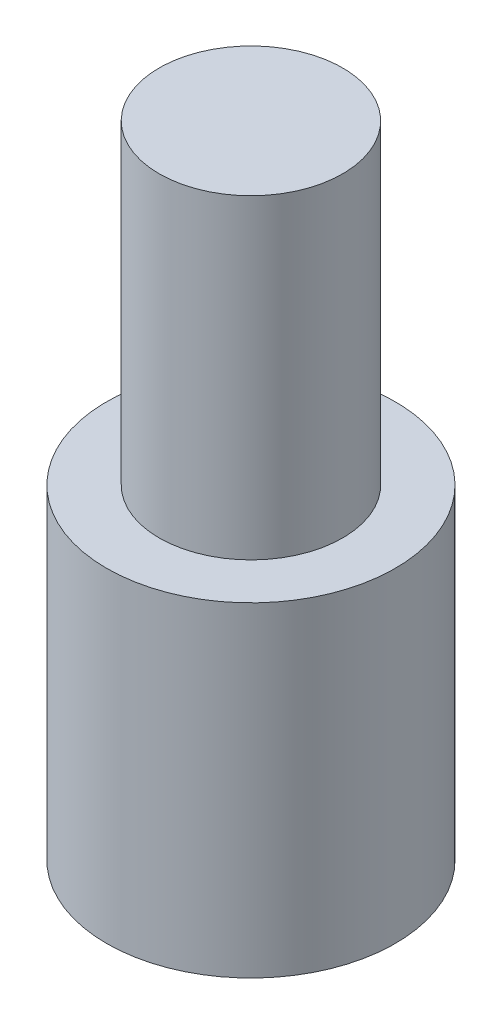
SolidWorks part; units mm, degrees
ref_plane "前视基准面" through (0, 0, 0) normal (0, 0, 1) x (1, 0, 0)
ref_plane "上视基准面" through (0, 0, 0) normal (0, 1, 0) x (1, 0, 0)
ref_plane "右视基准面" through (0, 0, 0) normal (1, 0, 0) x (0, 0, -1)
sketch "草图1" plane through (0, 0, 0) normal (0, 1, 0) x (1, 0, 0)
  circle A0 centre (-14.4643, 6.7518) radius 7.55
  dimension "D1" = 15.1
extrude "凸台-拉伸1" add sketch "草图1" along normal blind 17
sketch "草图2" plane through (0, 0, 0) normal (0, -1, 0) x (1, 0, 0)
  circle A0 centre (-14.4643, -6.7518) radius 5.15
  circle A1 centre (-14.4643, -6.7518) radius 7.55 construction
  point P2 (0, 0)
  dimension "D1" = 10.3
extrude "切除-拉伸1" cut sketch "草图2" against normal blind 2
sketch "草图3" plane through (0, 17, 0) normal (0, 1, 0) x (1, 0, 0)
  circle A0 centre (-14.4643, 6.7518) radius 4.8
  circle A1 centre (-14.4643, 6.7518) radius 7.55 construction
  dimension "D1" = 9.6
extrude "凸台-拉伸2" add sketch "草图3" along normal blind 16.5
